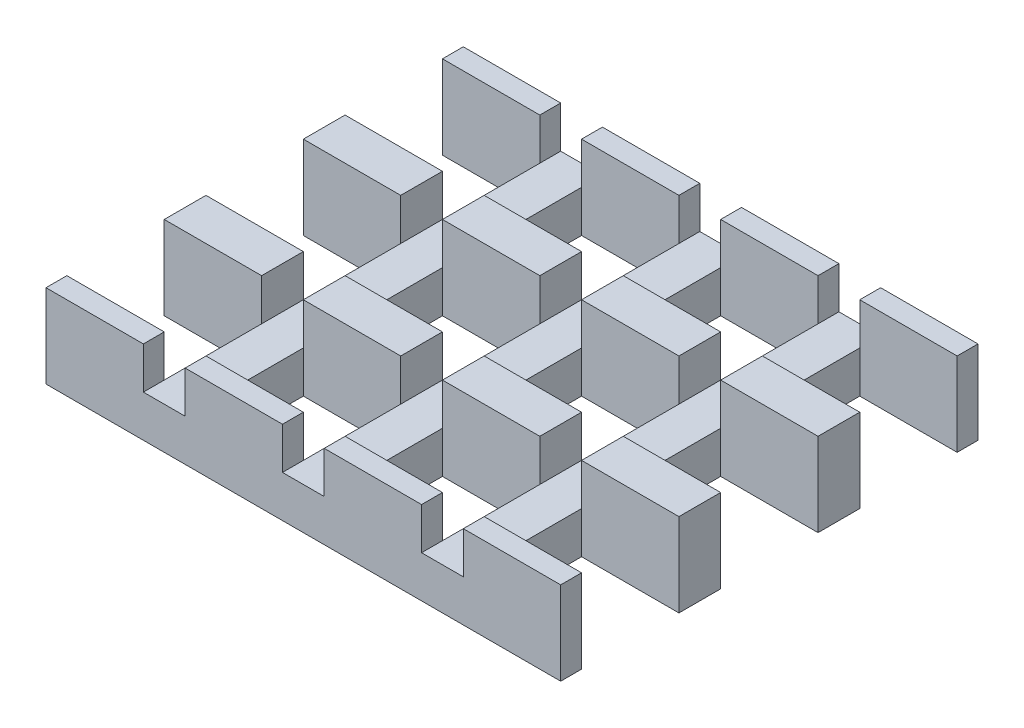
SolidWorks part; units mm, degrees
ref_plane "Front Plane" through (0, 0, 0) normal (0, 0, 1) x (1, 0, 0)
ref_plane "Top Plane" through (0, 0, 0) normal (0, 1, 0) x (1, 0, 0)
ref_plane "Right Plane" through (0, 0, 0) normal (1, 0, 0) x (0, 0, -1)
sketch "Sketch6" plane through (0, 0, 0) normal (0, 1, 0) x (1, 0, 0)
  line L1 (0, 0) -> (40, 0)
  line L2 (0, 0) -> (0, -30)
  line L3 (0, -30) -> (40, -30)
  line L4 (40, 0) -> (40, -30)
extrude "Boss-Extrude1" add sketch "Sketch6" along normal blind 6
sketch "Sketch10" plane through (0, 6, 0) normal (0, 1, 0) x (1, 0, 0)
  line L0 (0, 0) -> (1.5, 0) construction
  line L1 (40, 0) -> (0, 0) construction
  line L2 (1.5, 0) -> (1.5, -1.5) construction
  line L4 (1.5, -1.5) -> (8.5, -1.5)
  line L5 (1.5, -1.5) -> (1.5, -8.5)
  line L6 (1.5, -8.5) -> (8.5, -8.5)
  line L7 (8.5, -1.5) -> (8.5, -8.5)
extrude "Cut-Extrude6" cut sketch "Sketch10" against normal through all
pattern_linear "LPattern3" count 3 spacing 10 along (0, 0, 1) count 4 spacing 10 along (1, 0, 0) of "Cut-Extrude6"
sketch "Sketch11" plane through (0, 6, 0) normal (0, 1, 0) x (1, 0, 0)
  line L0 (40, 0) -> (0, 0) construction
  line L1 (8.5, 0) -> (11.5, 0)
  line L2 (8.5, 0) -> (8.5, -30)
  line L3 (8.5, -30) -> (11.5, -30)
  line L4 (11.5, 0) -> (11.5, -30)
  line L5 (0, -30) -> (40, -30) construction
extrude "Cut-Extrude7" cut sketch "Sketch11" against normal blind 3
pattern_linear "LPattern4" count 3 spacing 10 along (1, 0, 0) of "Cut-Extrude7"
sketch "Sketch12" plane through (0, 6, 0) normal (0, 1, 0) x (1, 0, 0)
  line L0 (0, -30) -> (8.5, -30) construction
  line L1 (0, 0) -> (1.5, 0)
  line L2 (0, 0) -> (0, -30)
  line L3 (0, -30) -> (1.5, -30)
  line L4 (1.5, 0) -> (1.5, -30)
  line L5 (31.5, -30) -> (40, -30) construction
  line L6 (40, 0) -> (38.5, 0)
  line L7 (40, 0) -> (40, -30)
  line L8 (40, -30) -> (38.5, -30)
  line L9 (38.5, 0) -> (38.5, -30)
  line L10 (38.5, -28.5) -> (38.5, -21.5) construction
extrude "Cut-Extrude8" cut sketch "Sketch12" against normal through all
